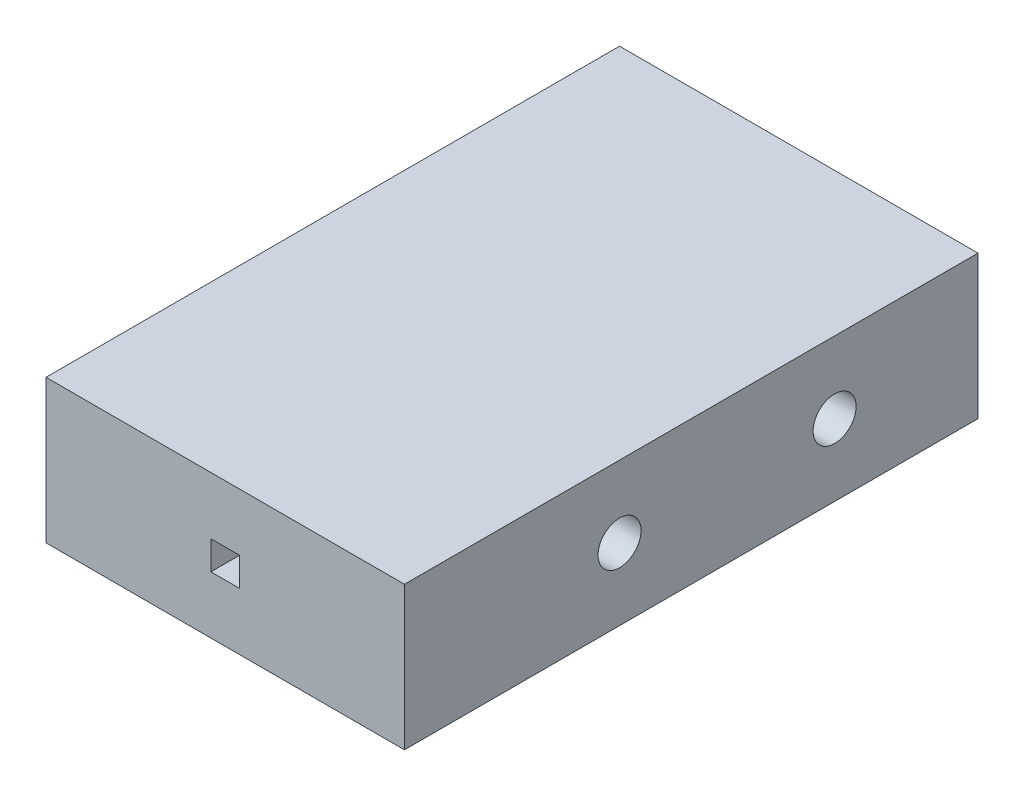
SolidWorks part; units mm, degrees
ref_plane "Plan de face" through (0, 0, 0) normal (0, 0, 1) x (1, 0, 0)
ref_plane "Plan de dessus" through (0, 0, 0) normal (0, 1, 0) x (1, 0, 0)
ref_plane "Plan de droite" through (0, 0, 0) normal (1, 0, 0) x (0, 0, -1)
sketch "Sketch1" plane through (0, 0, 0) normal (0, 1, 0) x (1, 0, 0)
  line L1 (12.5, -20) -> (-12.5, -20)
  line L2 (12.5, -20) -> (12.5, 20)
  line L3 (12.5, 20) -> (-12.5, 20)
  line L4 (-12.5, -20) -> (-12.5, 20)
  line L5 (12.5, -20) -> (-12.5, 20) construction
  line L6 (12.5, 20) -> (-12.5, -20) construction
  point P0 (0, 0)
  dimension "D1" = 25
  dimension "D2" = 40
extrude "Boss-Extrude1" add sketch "Sketch1" along normal blind 10
sketch "Sketch2" plane through (12.5, 0, 0) normal (1, 0, 0) x (0, 0, -1)
  line L0 (20, 10) -> (20, 0) construction
  line L1 (20, 0) -> (-20, 0) construction
  circle A0 centre (10, 5) radius 1.5
  dimension "D1" = 10
  dimension "D3" = 3
  dimension "D2" = 5
extrude "Cut-Extrude1" cut sketch "Sketch2" against normal through all
sketch "Sketch4" plane through (-12.5, 0, 0) normal (-1, 0, 0) x (0, 0, 1)
  line L0 (20, 10) -> (20, 0) construction
  line L1 (-20, 0) -> (20, 0) construction
  circle A0 centre (5, 5) radius 1.5
  point P2 (20, 5)
  dimension "D1" = 15
  dimension "D3" = 3
  dimension "D2" = 5
extrude "Cut-Extrude3" cut sketch "Sketch4" against normal through all
sketch "Sketch6" plane through (0, 0, 20) normal (0, 0, 1) x (1, 0, 0)
  line L0 (-12.5, 10) -> (-12.5, 0) construction
  line L1 (1, 4) -> (-1, 4)
  line L2 (1, 4) -> (1, 6)
  line L3 (1, 6) -> (-1, 6)
  line L4 (-1, 4) -> (-1, 6)
  line L5 (1, 4) -> (-1, 6) construction
  line L6 (1, 6) -> (-1, 4) construction
  point P0 (0, 5)
  dimension "D1" = 2
  dimension "D2" = 2
  dimension "D3" = 12.5
  dimension "D4" = 5
extrude "Cut-Extrude4" cut sketch "Sketch6" against normal through all
